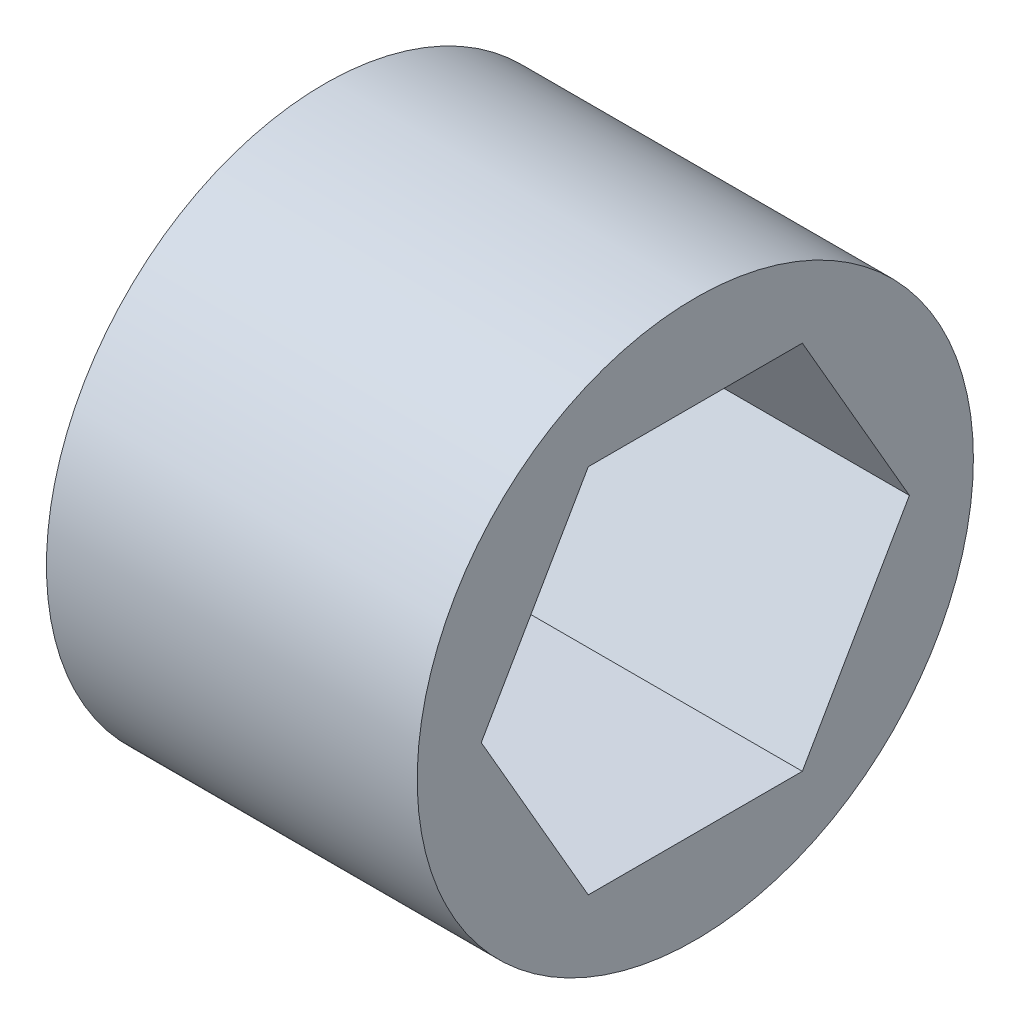
SolidWorks part; units mm, degrees
material "6063-T5"
ref_plane "Front" through (0, 0, 0) normal (0, 0, 1) x (1, 0, 0)
ref_plane "Top" through (0, 0, 0) normal (0, 1, 0) x (1, 0, 0)
ref_plane "Right" through (0, 0, 0) normal (1, 0, 0) x (0, 0, -1)
sketch "Sketch1" plane through (0, 0, 0) normal (1, 0, 0) x (0, 0, -1)
  line L1 (-3.6662, 6.35) -> (-7.3323, 0)
  line L2 (-7.3323, 0) -> (-3.6662, -6.35)
  line L3 (-3.6662, -6.35) -> (3.6662, -6.35)
  line L4 (3.6662, -6.35) -> (7.3323, 0)
  line L5 (7.3323, 0) -> (3.6662, 6.35)
  line L6 (3.6662, 6.35) -> (-3.6662, 6.35)
  circle A0 centre (0, 0) radius 6.35 construction
  circle A1 centre (0, 0) radius 9.525
  dimension "D2" = 19.05
  dimension "D1" = 12.7
extrude "Boss-Extrude1" add sketch "Sketch1" along normal blind 12.7
